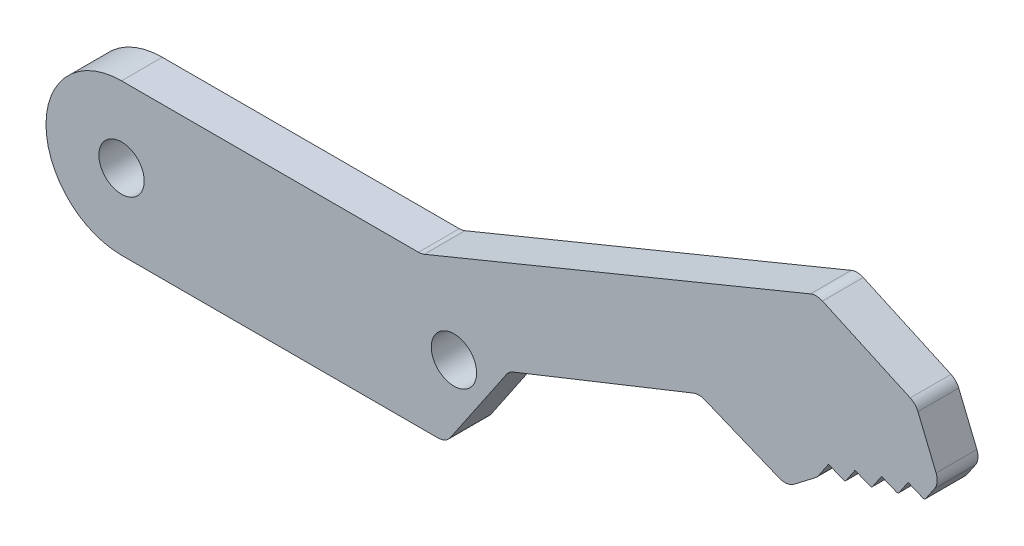
SolidWorks part; units mm, degrees
ref_plane "Front Plane" through (0, 0, 0) normal (0, 0, 1) x (1, 0, 0)
ref_plane "Top Plane" through (0, 0, 0) normal (0, 1, 0) x (1, 0, 0)
ref_plane "Right Plane" through (0, 0, 0) normal (1, 0, 0) x (0, 0, -1)
sketch "Sketch1" plane through (0, 0, 0) normal (0, 0, 1) x (1, 0, 0)
  line L0 (0, 5) -> (19.85, 5)
  line L1 (19.85, 5) -> (45.9962, 15.75)
  line L2 (45.9962, 15.75) -> (52.5575, 12.7612)
  line L3 (52.5575, 12.7612) -> (53.9075, 9.4779)
  line L4 (0, -5) -> (21.47, -5)
  line L5 (21.47, -5) -> (25.6444, 1.1586)
  line L6 (25.6444, 1.1586) -> (38.212, 6.17)
  line L7 (38.212, 6.17) -> (43.5199, 3.9974)
  line L8 (44.5077, 4.1297) -> (45.913, 5.2086)
  line L9 (46.1318, 5.4407) -> (46.7939, 6.4175)
  line L10 (46.7939, 6.4175) -> (47.8859, 5.9705)
  line L11 (47.8859, 5.9705) -> (48.548, 6.9472)
  line L12 (48.548, 6.9472) -> (49.64, 6.5003)
  line L13 (49.64, 6.5003) -> (50.3021, 7.477)
  line L14 (50.3021, 7.477) -> (51.3942, 7.03)
  line L15 (51.3942, 7.03) -> (52.0562, 8.0068)
  line L16 (52.0562, 8.0068) -> (53.1483, 7.5598)
  line L17 (53.1483, 7.5598) -> (53.8104, 8.5366)
  arc A0 (0, 5) -> (0, -5) centre (0, 0) ccw
  circle A1 centre (0, 0) radius 1.5
  circle A2 centre (22, 0) radius 1.5
  arc A3 (53.9075, 9.4779) -> (53.8104, 8.5366) centre (52.9826, 9.0976) cw
  arc A4 (45.913, 5.2086) -> (46.1318, 5.4407) centre (45.304, 6.0018) ccw
  arc A5 (43.5199, 3.9974) -> (44.5077, 4.1297) centre (43.8987, 4.9229) ccw
  point P30 (54.1117, 8.9811)
  point P35 (44.0518, 3.7797)
  dimension "D1" = 10
  dimension "D2" = 3
  dimension "D3" = 3
  dimension "D6" = 22
  dimension "D22" = 1
  dimension "D23" = 1
  dimension "D24" = 1
  dimension "D4" = 157.65
  dimension "D5" = 10.75
  dimension "D7" = 124.13
  dimension "D8" = 133.16
  dimension "D9" = 1.18
  dimension "D10" = 7.21
  dimension "D11" = 3.55
  dimension "D12" = 7.44
  dimension "D13" = 21.47
  dimension "D14" = 19.85
  dimension "D15" = 214.13
  dimension "D16" = 224
  dimension "D17" = 13.53
  dimension "D18" = 6.31
  dimension "D19" = 1.18
  dimension "D20" = 1.18
  dimension "D21" = 136.84
extrude "Boss-Extrude1" add sketch "Sketch1" against normal blind 2.7
fillet "Fillet1" radius 0.15 4 edges at (47.8859, 5.9705, -1.35) (49.64, 6.5003, -1.35) (53.1483, 7.5598, -1.35) (51.3942, 7.03, -1.35)
fillet "Fillet2" radius 1 3 edges at (21.47, -5, -1.35) (52.5575, 12.7612, -1.35) (45.9962, 15.75, -1.35)
fillet "Fillet3" radius 1 2 edges at (25.6444, 1.1586, -1.35) (38.212, 6.17, -1.35)
fillet "Fillet4" radius 1 1 edges at (19.85, 5, -1.35)
scale "Scale1" scale about centroid uniform scaling yes scale factor 1.9
